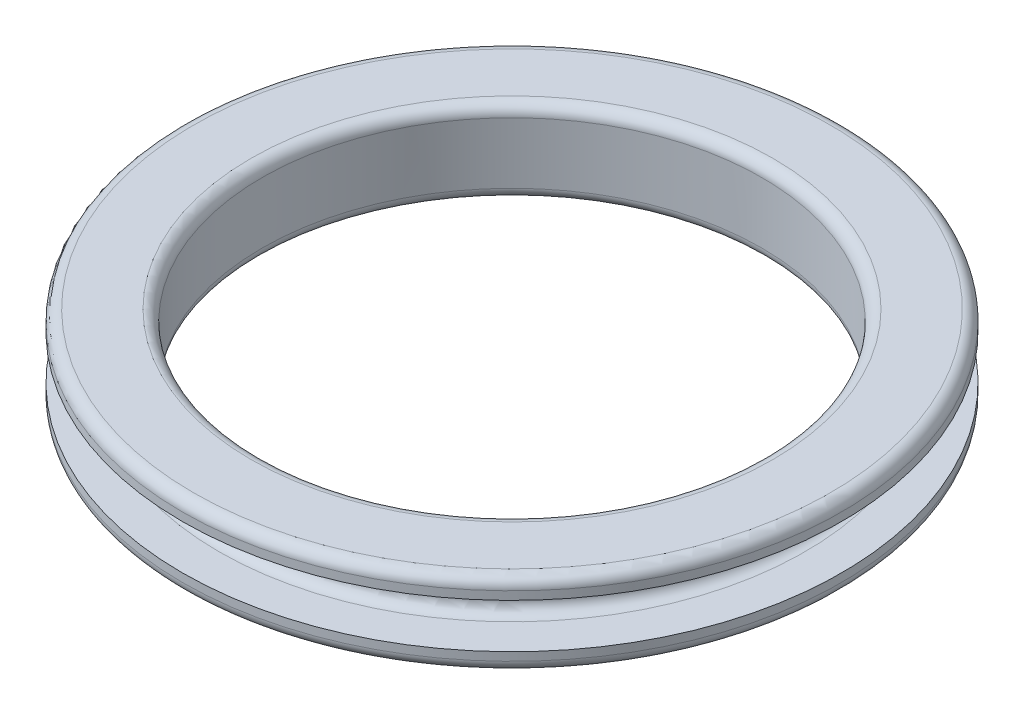
SolidWorks part; units mm, degrees
ref_plane "Front Plane" through (0, 0, 0) normal (0, 0, 1) x (1, 0, 0)
ref_plane "Top Plane" through (0, 0, 0) normal (0, 1, 0) x (1, 0, 0)
ref_plane "Right Plane" through (0, 0, 0) normal (1, 0, 0) x (0, 0, -1)
sketch "Sketch1" plane through (0, 0, 0) normal (0, 0, 1) x (1, 0, 0)
  line L0 (-9, 0) -> (-9, 3)
  line L1 (-9, 3) -> (-11.8718, 3)
  line L2 (-11.8718, 3) -> (-11.8718, 2.3)
  line L3 (-11.8718, 2.3) -> (-10.1534, 2.3)
  line L4 (-10.1534, 2.3) -> (-10.1534, 0.7)
  line L5 (-10.1534, 0.7) -> (-11.8718, 0.7)
  line L6 (-11.8718, 0.7) -> (-11.8718, 0)
  line L7 (-11.8718, 0) -> (-9, 0)
  line L8 (0, 7.2469) -> (0, -5.278) construction
  dimension "D1" = 9
  dimension "D2" = 3
  dimension "D3" = 0.7
  dimension "D4" = 0.7
  dimension "D5" = 1.6
revolve "Revolve1" add sketch "Sketch1" angle 360 about L8
fillet "Fillet1" radius 0.4 6 edges at (0, 3, 11.8718) (0, 0, 11.8718) (0, 0, 9) (0, 3, 9) (0, 0.7, 10.1534) (0, 2.3, 10.1534)
